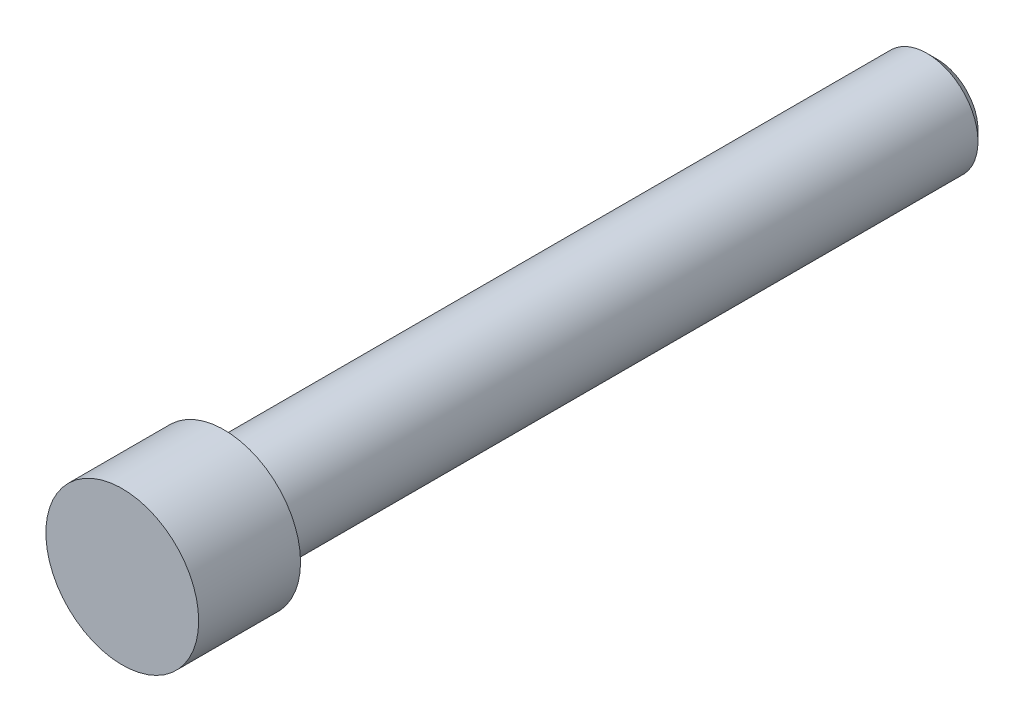
SolidWorks part; units mm, degrees
ref_plane "Alzado" through (0, 0, 0) normal (0, 0, 1) x (1, 0, 0)
ref_plane "Planta" through (0, 0, 0) normal (0, 1, 0) x (1, 0, 0)
ref_plane "Vista lateral" through (0, 0, 0) normal (1, 0, 0) x (0, 0, -1)
sketch "Croquis1" plane through (0, 0, 0) normal (0, 0, 1) x (1, 0, 0)
  circle A0 centre (0, 0) radius 1
  dimension "D1" = 2
extrude "Saliente-Extruir1" add sketch "Croquis1" along normal blind 14
sketch "Croquis2" plane through (0, 0, 14) normal (0, 0, 1) x (1, 0, 0)
  circle A0 centre (0, 0) radius 1.5
  dimension "D1" = 3
extrude "Saliente-Extruir2" add sketch "Croquis2" along normal blind 2
chamfer "Chaflán1" distance 0.2 angle 45 1 edges at (1, 0, 0)
